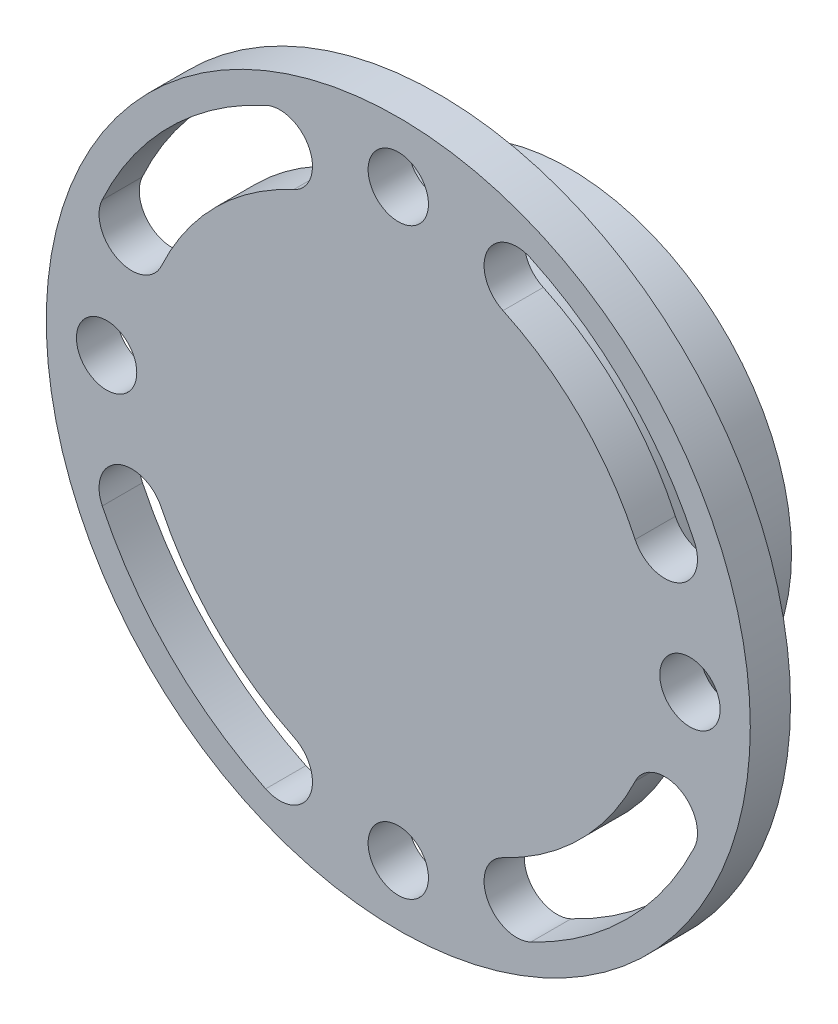
SolidWorks part; units mm, degrees
ref_plane "前视基准面" through (0, 0, 0) normal (0, 0, 1) x (1, 0, 0)
ref_plane "上视基准面" through (0, 0, 0) normal (0, 1, 0) x (1, 0, 0)
ref_plane "右视基准面" through (0, 0, 0) normal (1, 0, 0) x (0, 0, -1)
sketch "草图1" plane through (0, 0, 0) normal (0, 0, 1) x (1, 0, 0)
  circle A0 centre (0, 0) radius 20.1
  circle A1 centre (0, 0) radius 22.1
extrude "凸台-拉伸1" add sketch "草图1" against normal blind 13
sketch "草图3" plane through (0, 0, 0) normal (0, 0, 1) x (1, 0, 0)
  circle A0 centre (0, 0) radius 35
extrude "凸台-拉伸2" add sketch "草图3" along normal blind 4 contours A0
sketch "草图4" plane through (0, 0, 0) normal (0, 0, 1) x (1, 0, 0)
  circle A0 centre (0, 0) radius 16
sketch "草图5" plane through (0, 0, 0) normal (0, 0, 1) x (1, 0, 0)
  line L0 (0, 35) -> (0, 23)
  line L1 (-35, 0) -> (-23, 0)
  line L2 (0, -35) -> (0, -23)
  line L3 (35, 0) -> (23, 0)
  line L4 (0, 26.5) -> (17.0294, 26.5)
  line L5 (17.0294, 26.5) -> (-17.0294, 26.5)
  line L6 (-26.5, 0) -> (-26.5, 11.7792)
  line L7 (-26.5, 11.7792) -> (-26.5, -11.7792)
  line L8 (26.5, 0) -> (26.5, 11.7792)
  line L9 (26.5, 11.7792) -> (26.5, -11.7792)
  line L10 (0, -26.5) -> (11.7792, -26.5)
  line L11 (11.7792, -26.5) -> (-11.7792, -26.5)
  circle A0 centre (0, 0) radius 35 construction
  circle A1 centre (0, 29) radius 2.5
  circle A2 centre (29, 0) radius 2.5
  circle A3 centre (-29, 0) radius 2.5
  circle A4 centre (0, -29) radius 2.5
  circle A5 centre (0, 0) radius 29
  circle A6 centre (0, 0) radius 26.5
  circle A7 centre (0, 0) radius 31.5
sketch "草图6" plane through (0, 0, 0) normal (0, 0, 1) x (1, 0, 0)
  line L0 (0, 26.5) -> (11.7792, 26.5)
  line L1 (0, 26.5) -> (17.0294, 26.5) construction
  line L2 (0, 26.5) -> (-11.7792, 26.5)
  line L3 (17.0294, 26.5) -> (-17.0294, 26.5) construction
  line L4 (11.7792, 26.5) -> (10.7638, 24.2155)
  line L5 (10.7638, 24.2155) -> (12.7947, 28.7845)
  line L6 (-11.7792, 26.5) -> (-10.7638, 24.2155)
  line L7 (-10.7638, 24.2155) -> (-12.7947, 28.7845)
  line L8 (-26.5, 11.7792) -> (-24.2155, 10.7638)
  line L9 (-24.2155, 10.7638) -> (-28.7845, 12.7947)
  line L10 (-26.5, -11.7792) -> (-24.2155, -10.7638)
  line L11 (-24.2155, -10.7638) -> (-28.7845, -12.7947)
  line L12 (-11.7792, -26.5) -> (-10.7638, -24.2155)
  line L13 (-10.7638, -24.2155) -> (-12.7947, -28.7845)
  line L14 (11.7792, -26.5) -> (10.7638, -24.2155)
  line L15 (10.7638, -24.2155) -> (12.7947, -28.7845)
  line L16 (26.5, 11.7792) -> (28.7845, 12.7947)
  line L17 (28.7845, 12.7947) -> (24.2155, 10.7638)
  line L18 (26.5, -11.7792) -> (28.7845, -12.7947)
  line L19 (28.7845, -12.7947) -> (24.2155, -10.7638)
  circle A0 centre (0, 0) radius 29 construction
  circle A1 centre (0, 0) radius 26.5 construction
  circle A2 centre (0, 0) radius 31.5 construction
  arc A3 (-11.7792, 26.5) -> (-26.5, 11.7792) centre (0.6673, -0.6673) ccw construction
  arc A4 (-13.1329, 29.4547) -> (-29.4547, 13.1329) centre (0.6673, -0.6673) ccw
  arc A5 (-10.4256, 23.5453) -> (-23.5453, 10.4256) centre (0.6673, -0.6673) ccw
  arc A6 (-10.4256, 23.5453) -> (-13.1329, 29.4547) centre (-11.7792, 26.5) ccw
  arc A7 (-29.4547, 13.1329) -> (-23.5453, 10.4256) centre (-26.5, 11.7792) ccw
  arc A8 (11.7792, 26.5) -> (26.5, 11.7792) centre (-0.9443, -0.9443) cw construction
  arc A9 (29.4485, 13.1462) -> (13.1462, 29.4485) centre (-0.9443, -0.9443) ccw
  arc A10 (23.5515, 10.4122) -> (10.4122, 23.5515) centre (-0.9443, -0.9443) ccw
  arc A11 (23.5515, 10.4122) -> (29.4485, 13.1462) centre (26.5, 11.7792) ccw
  arc A12 (13.1462, 29.4485) -> (10.4122, 23.5515) centre (11.7792, 26.5) ccw
  arc A13 (26.5, -11.7792) -> (11.7792, -26.5) centre (-1.5595, 1.5595) cw construction
  arc A14 (13.1745, -29.4352) -> (29.4352, -13.1745) centre (-1.5595, 1.5595) ccw
  arc A15 (10.3839, -23.5648) -> (23.5648, -10.3839) centre (-1.5595, 1.5595) ccw
  arc A16 (10.3839, -23.5648) -> (13.1745, -29.4352) centre (11.7792, -26.5) ccw
  arc A17 (29.4352, -13.1745) -> (23.5648, -10.3839) centre (26.5, -11.7792) ccw
  arc A18 (-11.7792, -26.5) -> (-26.5, -11.7792) centre (1.8719, 1.8719) cw construction
  arc A19 (-29.4286, -13.1883) -> (-13.1883, -29.4286) centre (1.8719, 1.8719) ccw
  arc A20 (-23.5714, -10.3701) -> (-10.3701, -23.5714) centre (1.8719, 1.8719) ccw
  arc A21 (-23.5714, -10.3701) -> (-29.4286, -13.1883) centre (-26.5, -11.7792) ccw
  arc A22 (-13.1883, -29.4286) -> (-10.3701, -23.5714) centre (-11.7792, -26.5) ccw
  point P43 (-20.463, 20.463)
  point P48 (20.4459, 20.4459)
  point P54 (20.4093, -20.4093)
  point P60 (-20.3915, -20.3915)
extrude "切除-拉伸2" cut sketch "草图6" along normal blind 4
sketch "草图7" plane through (0, 0, 0) normal (0, 0, -1) x (-1, 0, 0)
  circle A0 centre (0, 29) radius 2.5
  circle A1 centre (29, 0) radius 2.5
  circle A2 centre (0, -29) radius 2.5
  circle A3 centre (-29, 0) radius 2.5
extrude "切除-拉伸3" cut sketch "草图7" against normal blind 4
sketch "草图8" plane through (0, 0, 0) normal (0, 0, 1) x (1, 0, 0)
  circle A0 centre (0, 29) radius 3
  circle A1 centre (-29, 0) radius 3
  circle A2 centre (0, -29) radius 3
  circle A3 centre (29, 0) radius 3
extrude "切除-拉伸4" cut sketch "草图8" along normal blind 4
ref_plane "基准面1" through (0, 0, -13) normal (0, 0, 1) x (1, 0, 0)
ref_plane "基准面2" through (0, 0, -11) normal (0, 0, -1) x (-1, 0, 0)
sketch "草图10" plane through (0, 0, -11) normal (0, 0, -1) x (-1, 0, 0)
  circle A0 centre (0, 0) radius 21.872
ref_plane "基准面3" through (0, 0, -6) normal (0, 0, -1) x (-1, 0, 0)
sketch "草图16" plane through (0, 0, -6) normal (0, 0, -1) x (-1, 0, 0)
  circle A0 centre (0, 0) radius 21.872
sketch "草图17" plane through (0, 0, 0) normal (1, 0, 0) x (0, 0, -1)
  circle A0 centre (3.5761, 1.1805) radius 42.2367
